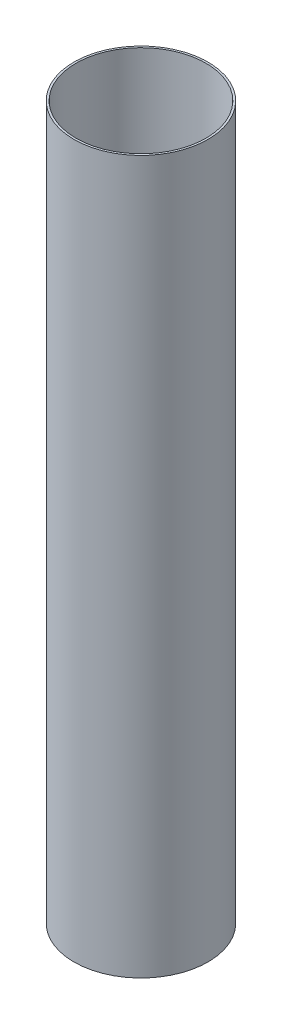
SolidWorks part; units mm, degrees
material "Hexcel AS4C (3000 Filaments)"
ref_plane "Front Plane" through (0, 0, 0) normal (0, 0, 1) x (1, 0, 0)
ref_plane "Top Plane" through (0, 0, 0) normal (0, 1, 0) x (1, 0, 0)
ref_plane "Right Plane" through (0, 0, 0) normal (1, 0, 0) x (0, 0, -1)
sketch "Sketch1" plane through (0, 0, 0) normal (0, 1, 0) x (1, 0, 0)
  circle A0 centre (0, 0) radius 52.578
  circle A1 centre (0, 0) radius 50.9905
  dimension "D1" = 101.981
  dimension "D2" = 1.5875
extrude "Boss-Extrude1" add sketch "Sketch1" along normal blind 558.8
equation "\"CF_OD_A\"= 4.015in"
equation "\"CF_ID_A\"= 3.904in"
equation "\"KF_ID_A\"= 4.015in ' Kevlar airframe ID"
equation "\"KF_WALL\"= 0.0625in"
equation "\"AF_01\"=10in"
equation "\"AF_02\"=22in"
equation "\"AF_03\"=56in"
equation "\"D1@Sketch1\"=\"KF_ID_A\""
equation "\"D2@Sketch1\"=\"KF_WALL\""
equation "\"D1@Boss-Extrude1\"=\"AF_02\""
